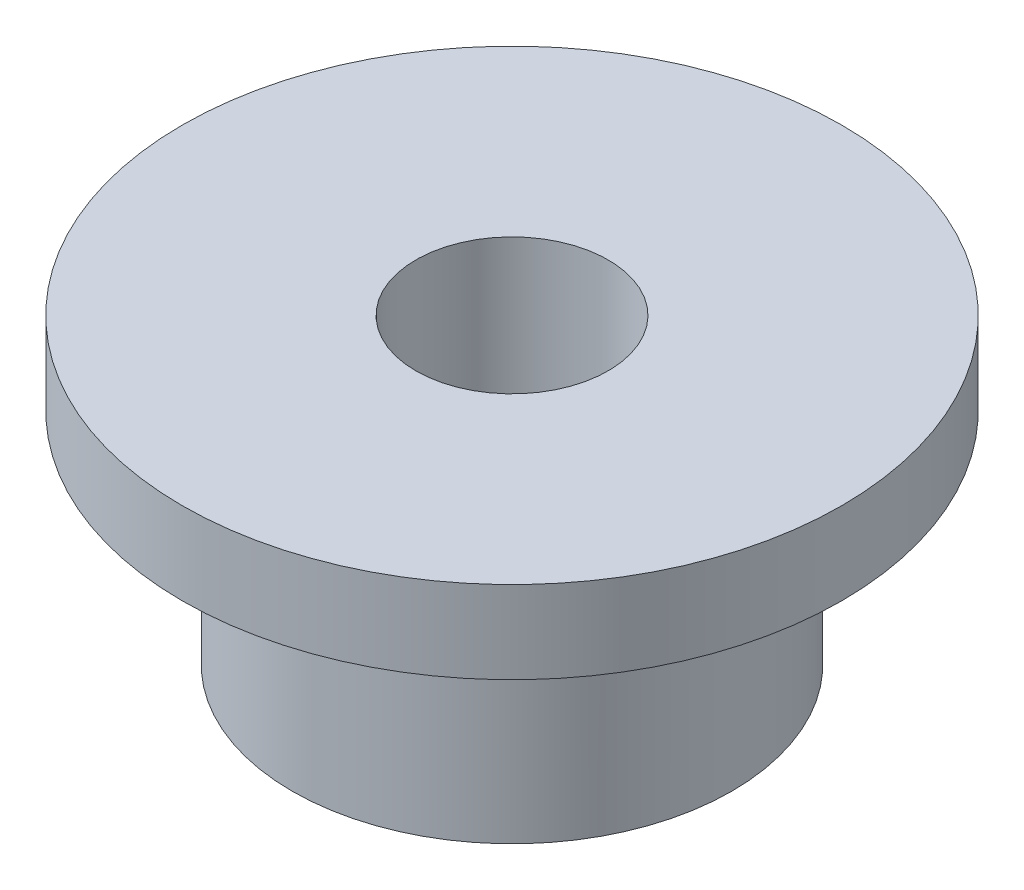
SolidWorks part; units mm, degrees
ref_plane "Спереди" through (0, 0, 0) normal (0, 0, 1) x (1, 0, 0)
ref_plane "Сверху" through (0, 0, 0) normal (0, 1, 0) x (1, 0, 0)
ref_plane "Справа" through (0, 0, 0) normal (1, 0, 0) x (0, 0, -1)
sketch "Эскиз1" plane through (0, 0, 0) normal (0, 1, 0) x (1, 0, 0)
  circle A0 centre (0, 0) radius 12
extrude "Вытянуть1" add sketch "Эскиз1" along normal blind 3
sketch "Эскиз2" plane through (0, 0, 0) normal (0, -1, 0) x (1, 0, 0)
  circle A0 centre (0, 0) radius 8
extrude "Вытянуть2" add sketch "Эскиз2" along normal blind 8
sketch "Эскиз3" plane through (0, 3, 0) normal (0, 1, 0) x (1, 0, 0)
  circle A0 centre (0, 0) radius 3.5
extrude "Вырез-Вытянуть1" cut sketch "Эскиз3" against normal blind 8
